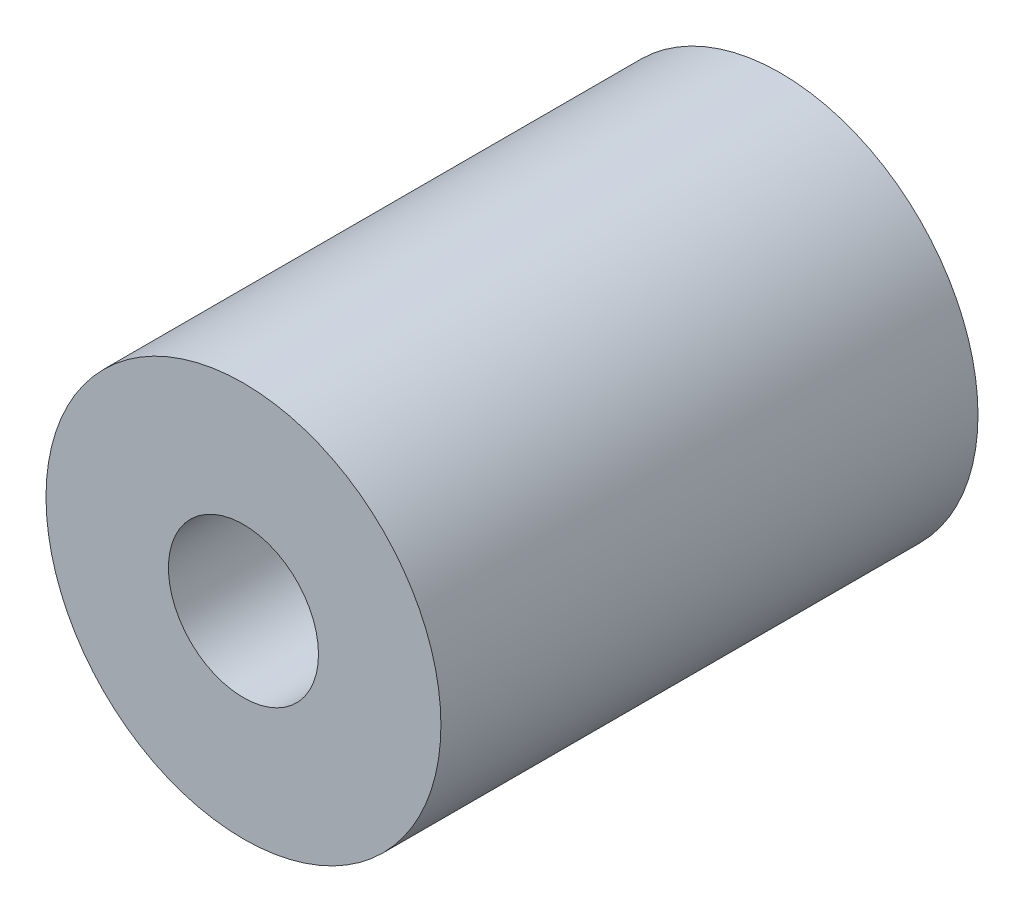
SolidWorks part; units mm, degrees
material "3.1355 (EN-AW 2024)"
ref_plane "Front Plane" through (0, 0, 0) normal (0, 0, 1) x (1, 0, 0)
ref_plane "Top Plane" through (0, 0, 0) normal (0, 1, 0) x (1, 0, 0)
ref_plane "Right Plane" through (0, 0, 0) normal (1, 0, 0) x (0, 0, -1)
sketch "Sketch1" plane through (0, 0, 0) normal (0, 1, 0) x (1, 0, 0)
  line L0 (6, -55) -> (25, -55)
  line L1 (25, -55) -> (25, -123)
  line L2 (25, -123) -> (9.5, -123)
  line L3 (9.5, -123) -> (9.5, -85)
  line L4 (9.5, -85) -> (20, -85)
  line L5 (20, -85) -> (20, -75)
  line L6 (20, -75) -> (6, -75)
  line L7 (6, -75) -> (6, -55)
  line L8 (0, -150) -> (0, 150) construction
revolve "REV_Bellows_Coupling_D50x68_bores_12_19" add sketch "Sketch1" angle 360 about L8
